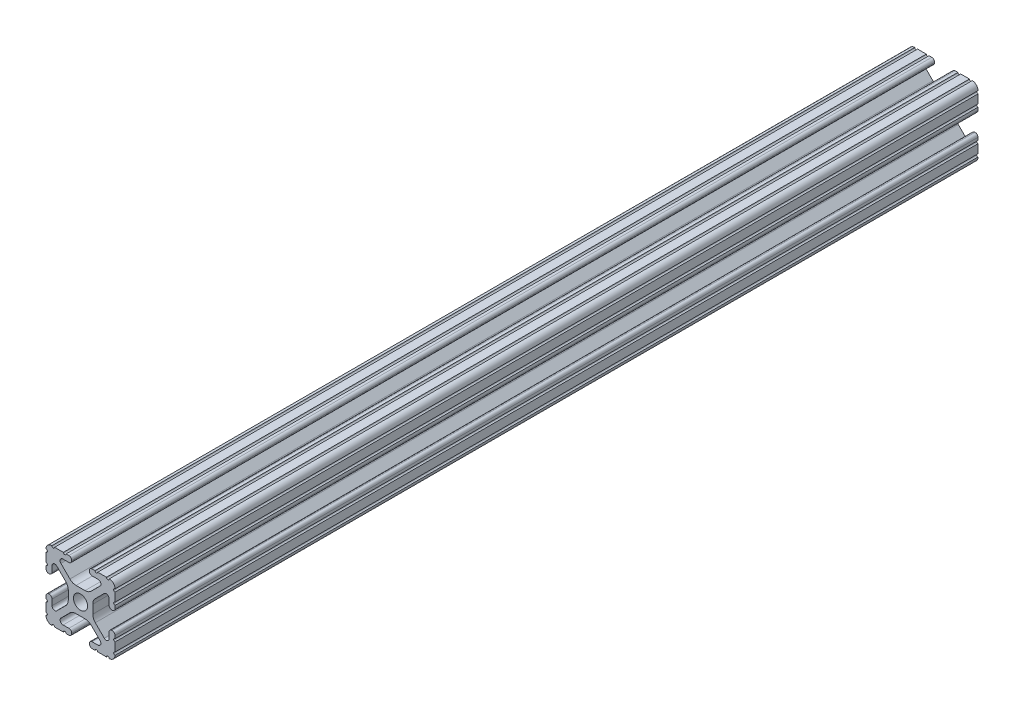
SolidWorks part; units mm, degrees
material "6105-T5 Aluminum"
ref_plane "Front Plane" through (0, 0, 0) normal (0, 0, 1) x (1, 0, 0)
ref_plane "Top Plane" through (0, 0, 0) normal (0, 1, 0) x (1, 0, 0)
ref_plane "Right Plane" through (0, 0, 0) normal (1, 0, 0) x (0, 0, -1)
sketch "Sketch1" plane through (0, 0, 0) normal (0, 0, 1) x (1, 0, 0)
  line L0 (-7.207, 8.7244) -> (-3.8983, 5.4232)
  line L1 (-4.2875, 10.4902) -> (-6.4768, 10.4902)
  line L2 (-3.2385, 11.651) -> (-3.2385, 11.5392)
  line L3 (-5.3171, 12.7) -> (-4.2875, 12.7)
  line L4 (0, 13.4005) -> (0, -14.8534) construction
  line L5 (12.7, 0) -> (-13.9989, 0) construction
  line L6 (-9.5504, 12.7) -> (-6.3331, 12.7)
  line L7 (-12.7, 6.3331) -> (-12.7, 9.5504)
  line L8 (-12.7, 4.2875) -> (-12.7, 5.3171)
  line L9 (-11.5392, 3.2385) -> (-11.651, 3.2385)
  line L10 (-10.4902, 6.4021) -> (-10.4902, 4.2875)
  line L11 (-5.441, 3.8408) -> (-8.7371, 7.1294)
  line L12 (-4.5085, -1.5932) -> (-4.5085, 1.5932)
  line L13 (-1.7093, -4.4958) -> (1.7093, -4.4958)
  line L14 (3.9523, -5.4237) -> (7.1797, -8.6452)
  line L15 (6.4164, -10.4902) -> (4.2875, -10.4902)
  line L16 (3.2385, -11.5392) -> (3.2385, -11.651)
  line L17 (4.2875, -12.7) -> (5.3171, -12.7)
  line L18 (6.3331, -12.7) -> (9.5504, -12.7)
  line L19 (12.7, -9.5504) -> (12.7, -6.3331)
  line L20 (12.7, -5.3171) -> (12.7, -4.2875)
  line L21 (11.651, -3.2385) -> (11.5392, -3.2385)
  line L22 (10.4902, -4.2875) -> (10.4902, -6.4021)
  line L23 (8.7371, -7.1294) -> (5.441, -3.8408)
  line L24 (4.5085, -1.5932) -> (4.5085, 1.5932)
  line L25 (5.441, 3.8408) -> (8.7371, 7.1294)
  line L26 (10.4902, 6.4021) -> (10.4902, 4.2875)
  line L27 (11.5392, 3.2385) -> (11.651, 3.2385)
  line L28 (12.7, 4.2875) -> (12.7, 5.3171)
  line L29 (12.7, 6.3331) -> (12.7, 9.5504)
  line L30 (9.5504, 12.7) -> (6.3331, 12.7)
  line L31 (5.3171, 12.7) -> (4.2875, 12.7)
  line L32 (3.2385, 11.651) -> (3.2385, 11.5392)
  line L33 (4.2875, 10.4902) -> (6.4768, 10.4902)
  line L34 (7.207, 8.7244) -> (3.8983, 5.4232)
  line L35 (1.6558, 4.4958) -> (-1.6558, 4.4958)
  line L36 (-8.7371, -7.1294) -> (-5.441, -3.8408)
  line L37 (-10.4902, -4.2875) -> (-10.4902, -6.4021)
  line L38 (-11.651, -3.2385) -> (-11.5392, -3.2385)
  line L39 (-12.7, -5.3171) -> (-12.7, -4.2875)
  line L40 (-12.7, -9.5504) -> (-12.7, -6.3331)
  line L41 (-6.3331, -12.7) -> (-9.5504, -12.7)
  line L42 (-4.2875, -12.7) -> (-5.3171, -12.7)
  line L43 (-3.2385, -11.5392) -> (-3.2385, -11.651)
  line L44 (-6.4164, -10.4902) -> (-4.2875, -10.4902)
  line L45 (-3.9523, -5.4237) -> (-7.1797, -8.6452)
  arc A0 (-7.207, 8.7244) -> (-6.4768, 10.4902) centre (-6.4768, 9.4563) cw
  arc A1 (-3.2385, 11.5392) -> (-4.2875, 10.4902) centre (-4.2875, 11.5392) cw
  arc A2 (-4.2875, 12.7) -> (-3.2385, 11.651) centre (-4.2875, 11.651) cw
  arc A3 (-5.3171, 12.7) -> (-6.3331, 12.7) centre (-5.8251, 12.7) cw
  arc A4 (-9.5504, 12.7) -> (-10.5664, 12.6998) centre (-10.0584, 12.7) cw
  arc A5 (-12.6998, 10.5664) -> (-10.5664, 12.6998) centre (-10.5918, 10.5918) cw
  arc A6 (-12.6998, 10.5664) -> (-12.7, 9.5504) centre (-12.7, 10.0584) cw
  arc A7 (-12.7, 6.3331) -> (-12.7, 5.3171) centre (-12.7, 5.8251) cw
  arc A8 (-11.651, 3.2385) -> (-12.7, 4.2875) centre (-11.651, 4.2875) cw
  arc A9 (-10.4902, 4.2875) -> (-11.5392, 3.2385) centre (-11.5392, 4.2875) cw
  circle A10 centre (0, 0) radius 2.6035
  arc A11 (-10.4902, 6.4021) -> (-8.7371, 7.1294) centre (-9.4628, 6.4021) cw
  arc A12 (-5.441, 3.8408) -> (-4.5085, 1.5932) centre (-7.6835, 1.5932) cw
  arc A13 (-4.5085, -1.5932) -> (-5.441, -3.8408) centre (-7.6835, -1.5932) cw
  arc A14 (-8.7371, -7.1294) -> (-10.4902, -6.4021) centre (-9.4628, -6.4021) cw
  arc A15 (-1.7093, -4.4958) -> (-3.9523, -5.4237) centre (-1.7093, -7.6708) ccw
  arc A16 (3.9523, -5.4237) -> (1.7093, -4.4958) centre (1.7093, -7.6708) ccw
  arc A17 (6.4164, -10.4902) -> (7.1797, -8.6452) centre (6.4164, -9.4098) ccw
  arc A18 (4.2875, -10.4902) -> (3.2385, -11.5392) centre (4.2875, -11.5392) ccw
  arc A19 (3.2385, -11.651) -> (4.2875, -12.7) centre (4.2875, -11.651) ccw
  arc A20 (6.3331, -12.7) -> (5.3171, -12.7) centre (5.8251, -12.7) ccw
  arc A21 (10.5664, -12.6998) -> (9.5504, -12.7) centre (10.0584, -12.7) ccw
  arc A22 (10.5664, -12.6998) -> (12.6998, -10.5664) centre (10.5918, -10.5918) ccw
  arc A23 (12.7, -9.5504) -> (12.6998, -10.5664) centre (12.7, -10.0584) ccw
  arc A24 (12.7, -5.3171) -> (12.7, -6.3331) centre (12.7, -5.8251) ccw
  arc A25 (12.7, -4.2875) -> (11.651, -3.2385) centre (11.651, -4.2875) ccw
  arc A26 (11.5392, -3.2385) -> (10.4902, -4.2875) centre (11.5392, -4.2875) ccw
  arc A27 (8.7371, -7.1294) -> (10.4902, -6.4021) centre (9.4628, -6.4021) ccw
  arc A28 (4.5085, -1.5932) -> (5.441, -3.8408) centre (7.6835, -1.5932) ccw
  arc A29 (5.441, 3.8408) -> (4.5085, 1.5932) centre (7.6835, 1.5932) ccw
  arc A30 (10.4902, 6.4021) -> (8.7371, 7.1294) centre (9.4628, 6.4021) ccw
  arc A31 (10.4902, 4.2875) -> (11.5392, 3.2385) centre (11.5392, 4.2875) ccw
  arc A32 (11.651, 3.2385) -> (12.7, 4.2875) centre (11.651, 4.2875) ccw
  arc A33 (12.7, 6.3331) -> (12.7, 5.3171) centre (12.7, 5.8251) ccw
  arc A34 (12.6998, 10.5664) -> (12.7, 9.5504) centre (12.7, 10.0584) ccw
  arc A35 (12.6998, 10.5664) -> (10.5664, 12.6998) centre (10.5918, 10.5918) ccw
  arc A36 (9.5504, 12.7) -> (10.5664, 12.6998) centre (10.0584, 12.7) ccw
  arc A37 (5.3171, 12.7) -> (6.3331, 12.7) centre (5.8251, 12.7) ccw
  arc A38 (4.2875, 12.7) -> (3.2385, 11.651) centre (4.2875, 11.651) ccw
  arc A39 (3.2385, 11.5392) -> (4.2875, 10.4902) centre (4.2875, 11.5392) ccw
  arc A40 (7.207, 8.7244) -> (6.4768, 10.4902) centre (6.4768, 9.4563) ccw
  arc A41 (1.6558, 4.4958) -> (3.8983, 5.4232) centre (1.6558, 7.6708) ccw
  arc A42 (-1.6558, 4.4958) -> (-3.8983, 5.4232) centre (-1.6558, 7.6708) cw
  arc A43 (-11.5392, -3.2385) -> (-10.4902, -4.2875) centre (-11.5392, -4.2875) cw
  arc A44 (-12.7, -4.2875) -> (-11.651, -3.2385) centre (-11.651, -4.2875) cw
  arc A45 (-12.7, -5.3171) -> (-12.7, -6.3331) centre (-12.7, -5.8251) cw
  arc A46 (-12.7, -9.5504) -> (-12.6998, -10.5664) centre (-12.7, -10.0584) cw
  arc A47 (-10.5664, -12.6998) -> (-12.6998, -10.5664) centre (-10.5918, -10.5918) cw
  arc A48 (-10.5664, -12.6998) -> (-9.5504, -12.7) centre (-10.0584, -12.7) cw
  arc A49 (-6.3331, -12.7) -> (-5.3171, -12.7) centre (-5.8251, -12.7) cw
  arc A50 (-3.2385, -11.651) -> (-4.2875, -12.7) centre (-4.2875, -11.651) cw
  arc A51 (-4.2875, -10.4902) -> (-3.2385, -11.5392) centre (-4.2875, -11.5392) cw
  arc A52 (-6.4164, -10.4902) -> (-7.1797, -8.6452) centre (-6.4164, -9.4098) cw
  dimension "D1" = 5.207
  dimension "D9" = 14.859
  dimension "D2" = 25.4
  dimension "D3" = 12.7
  dimension "D4" = 6.477
  dimension "D5" = 8.2042
  dimension "D6" = 9.017
  dimension "D8" = 2.2098
  dimension "D10" = 2.2098
extrude "Extrude1" add sketch "Sketch1" against normal blind 317.5
